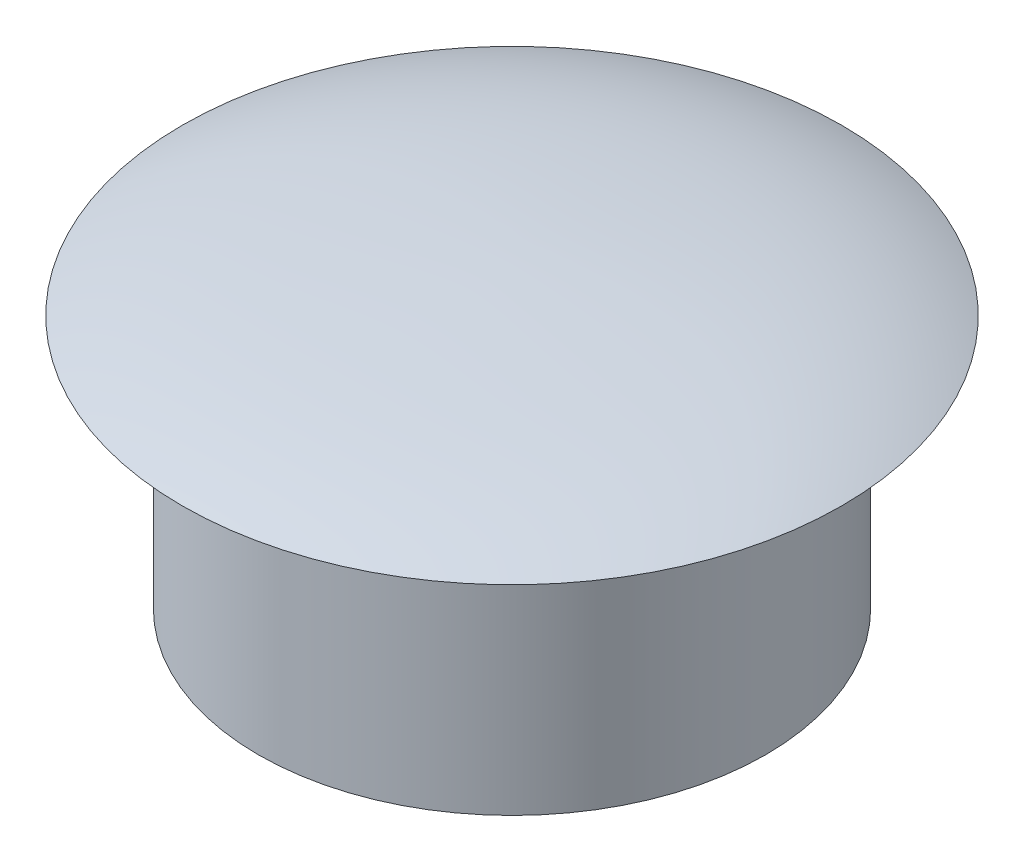
SolidWorks part; units mm, degrees
ref_plane "Front Plane" through (0, 0, 0) normal (0, 0, 1) x (1, 0, 0)
ref_plane "Top Plane" through (0, 0, 0) normal (0, 1, 0) x (1, 0, 0)
ref_plane "Right Plane" through (0, 0, 0) normal (1, 0, 0) x (0, 0, -1)
sketch "Sketch1" plane through (0, 0, 0) normal (0, 0, 1) x (1, 0, 0)
  line L0 (-4.2477, 9.5751) -> (-5.2477, 9.5751)
  line L1 (-5.2477, 9.5751) -> (-5.2477, 14.5751)
  line L2 (-5.2477, 14.5751) -> (-6.7477, 14.5751)
  line L3 (-0.2477, 15.5125) -> (-0.2477, 14.5751)
  line L4 (-4.2477, 9.5751) -> (-4.2477, 14.5751)
  line L5 (-4.2477, 14.5751) -> (-0.2477, 14.5751)
  spline S0 degree 3 poles (-6.7477, 14.5751) (-5.6564, 15.056) (-3.6053, 15.3884) (-1.0433, 15.5125) (-0.2477, 15.5125) knots 0 0 0 0 0.533518 1 1 1 1
  dimension "D1" = 1
  dimension "D2" = 5
  dimension "D3" = 5
  dimension "D4" = 5
  dimension "D5" = 6.5
revolve "Revolve1" add sketch "Sketch1" angle 360 about L3
